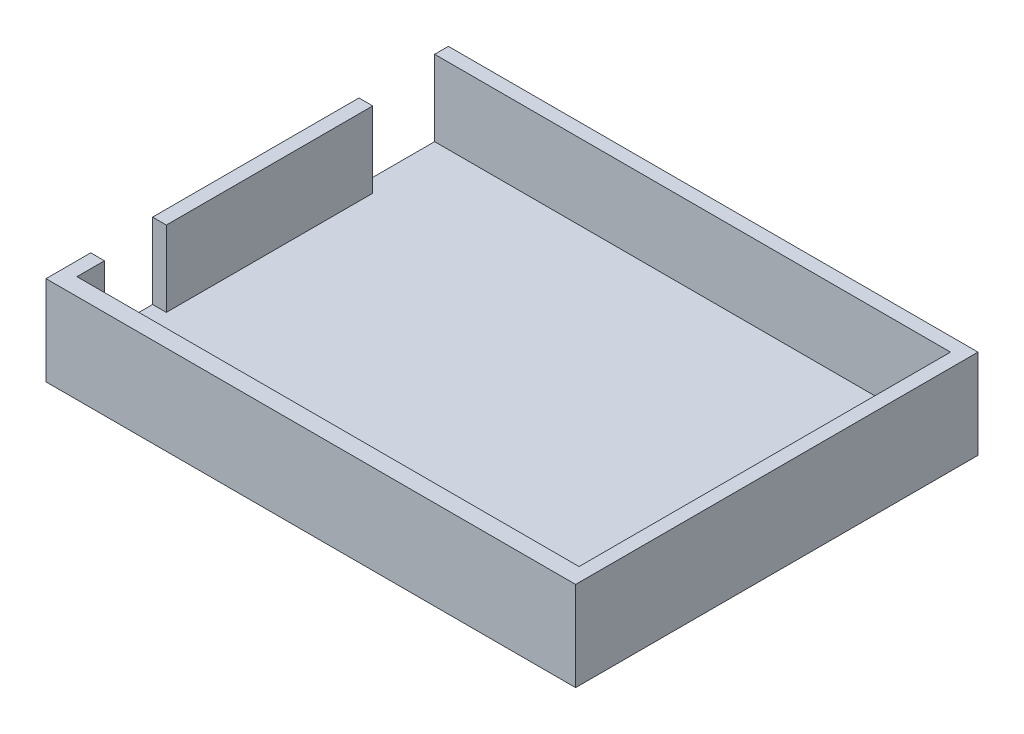
SolidWorks part; units mm, degrees
ref_plane "前视基准面" through (0, 0, 0) normal (0, 0, 1) x (1, 0, 0)
ref_plane "上视基准面" through (0, 0, 0) normal (0, 1, 0) x (1, 0, 0)
ref_plane "右视基准面" through (0, 0, 0) normal (1, 0, 0) x (0, 0, -1)
sketch "草图1" plane through (0, 0, 0) normal (0, 1, 0) x (1, 0, 0)
  line L0 (-38.5, 29.25) -> (38.5, 29.25)
  line L1 (-36.5, -27.25) -> (36.5, -27.25) construction
  line L2 (-36.5, -27.25) -> (-36.5, 27.25) construction
  line L3 (-36.5, 27.25) -> (36.5, 27.25) construction
  line L4 (36.5, -27.25) -> (36.5, 27.25) construction
  line L5 (-36.5, -27.25) -> (36.5, 27.25) construction
  line L6 (-36.5, 27.25) -> (36.5, -27.25) construction
  line L7 (38.5, -29.25) -> (38.5, 29.25)
  line L8 (-38.5, -29.25) -> (38.5, -29.25)
  line L9 (-38.5, -29.25) -> (-38.5, 29.25)
  point P0 (0, 0)
  dimension "D1" = 73
  dimension "D2" = 54.5
  dimension "D3" = 2
extrude "凸台-拉伸1" add sketch "草图1" along normal blind 2
sketch "草图2" plane through (0, 2, 0) normal (0, 1, 0) x (1, 0, 0)
  line L1 (-36.5, -26.75) -> (36.5, -26.75)
  line L2 (-36.5, -26.75) -> (-36.5, 27.25)
  line L3 (-36.5, 27.25) -> (36.5, 27.25)
  line L4 (36.5, -26.75) -> (36.5, 27.25)
  line L5 (-36.5, -26.75) -> (36.5, 27.25) construction
  line L6 (-36.5, 27.25) -> (36.5, -26.75) construction
  line L8 (-38.5, -29.25) -> (38.5, -29.25)
  line L9 (-38.5, -29.25) -> (-38.5, 29.25)
  line L10 (-38.5, 29.25) -> (38.5, 29.25)
  line L11 (38.5, -29.25) -> (38.5, 29.25)
  line L12 (-38.5, -29.25) -> (38.5, 29.25) construction
  line L13 (-38.5, 29.25) -> (38.5, -29.25) construction
  point P0 (0, 0)
extrude "凸台-拉伸2" add sketch "草图2" along normal blind 11
sketch "草图3" plane through (-38.5, 0, 0) normal (-1, 0, 0) x (0, 0, 1)
  line L0 (22.75, 13) -> (22.75, 2) construction
  line L1 (-29.25, 13) -> (29.25, 13) construction
  line L3 (29.25, 13) -> (29.25, 0) construction
  line L4 (-27.25, 13) -> (-27.25, 2) construction
  line L5 (22.75, 13) -> (13.75, 13)
  line L6 (22.75, 13) -> (22.75, 2)
  line L8 (13.75, 13) -> (13.75, 2)
  line L9 (-29.25, 0) -> (29.25, 0) construction
  line L10 (-29.25, 13) -> (-29.25, 0) construction
  line L11 (-27.25, 2) -> (-16.25, 2)
  line L12 (-27.25, 13) -> (-16.25, 13)
  line L13 (-27.25, 13) -> (-27.25, 2)
  line L14 (13.75, 2) -> (22.75, 2)
  line L15 (-16.25, 13) -> (-16.25, 2)
  dimension "D1" = 6.5
  dimension "D2" = 15.5
  dimension "D3" = 2
  dimension "D4" = 11
  dimension "D5" = 2
extrude "切除-拉伸1" cut sketch "草图3" against normal up to next
